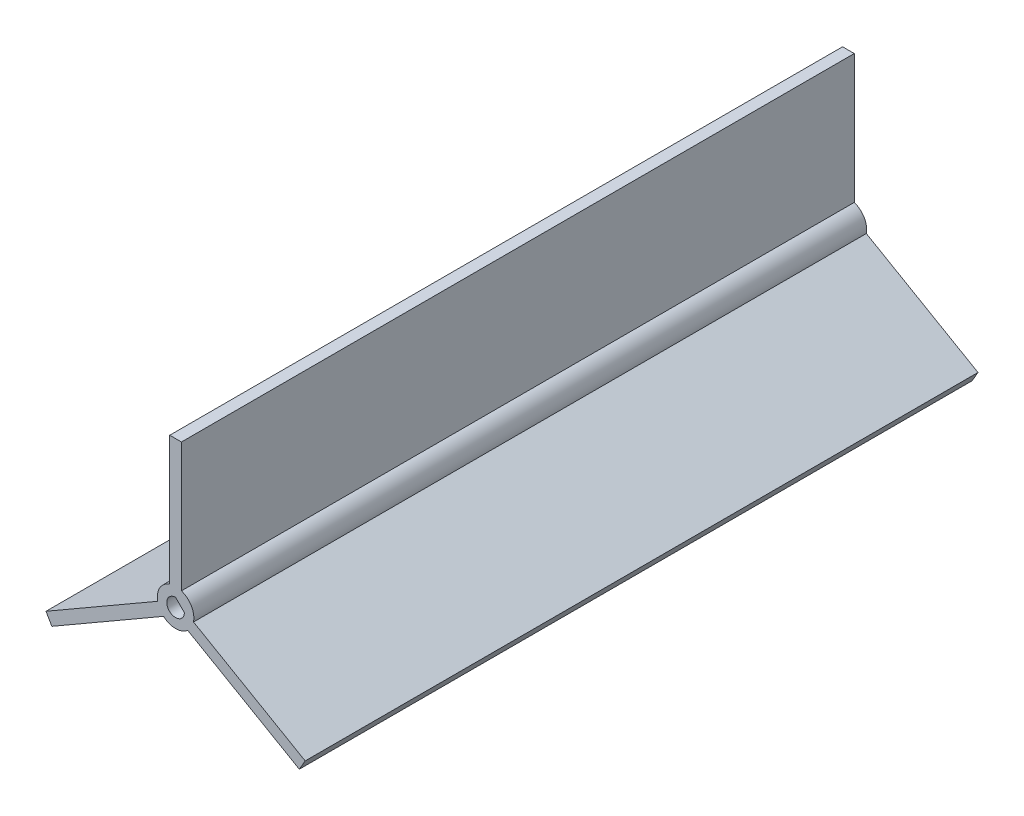
SolidWorks part; units mm, degrees
material "ABS"
ref_plane "Front Plane" through (0, 0, 0) normal (0, 0, 1) x (1, 0, 0)
ref_plane "Top Plane" through (0, 0, 0) normal (0, 1, 0) x (1, 0, 0)
ref_plane "Right Plane" through (0, 0, 0) normal (1, 0, 0) x (0, 0, -1)
sketch "Sketch1" plane through (0, 0, 0) normal (0, 0, 1) x (1, 0, 0)
  line L0 (0, 0) -> (0, 63.5)
  line L1 (0, 0) -> (54.9926, -31.75)
  line L2 (54.9926, -31.75) -> (0, 0)
  line L3 (0, 0) -> (-54.9926, -31.75)
  line L4 (2.54, 1.4665) -> (2.54, 63.5)
  line L5 (-2.54, 1.4665) -> (-56.2626, -29.5503)
  line L6 (-2.54, 1.4665) -> (-2.54, 63.5)
  line L7 (0, -2.9329) -> (-53.7226, -33.9497)
  line L8 (0, -2.9329) -> (53.7226, -33.9497)
  line L9 (2.54, 1.4665) -> (56.2626, -29.5503)
  line L10 (1.27, -2.1997) -> (-53.7226, -33.9497) construction
  line L11 (-1.27, -2.1997) -> (53.7226, -33.9497) construction
  line L12 (-1.27, 2.1997) -> (-56.2626, -29.5503) construction
  line L13 (-2.54, 0) -> (-2.54, 63.5) construction
  line L14 (1.27, 2.1997) -> (56.2626, -29.5503) construction
  line L15 (2.54, 0) -> (2.54, 63.5) construction
  line L16 (56.2626, -29.5503) -> (53.7226, -33.9497)
  line L17 (-56.2626, -29.5503) -> (-53.7226, -33.9497)
  line L18 (-2.54, 63.5) -> (2.54, 63.5)
  circle A0 centre (0, 0) radius 63.5 construction
  circle A1 centre (0, 0) radius 7.9375
  dimension "D1" = 120
  dimension "D3" = 127
  dimension "D4" = 15.875
  dimension "D2" = 120
  dimension "D5" = 2.54
  dimension "D6" = 2.54
  dimension "D7" = 2.54
  dimension "D8" = 2.54
extrude "Boss-Extrude1" add sketch "Sketch1" along normal blind 292.1 contours L6 A1 L5 | L7 A1 L8 | L9 A1 L4 | L3 A1 L7 L8 L1 | L0 A1 L6 L5 L3 | L4 A1 L0 L1 L9 | A1 L4 L18 L0 | A1 L0 L18 L6 | A1 L5 L17 L3 | A1 L3 L17 L7 | A1 L8 L16 L2 | A1 L2 L16 L9
sketch "Sketch2" plane through (0, 0, 292.1) normal (0, 0, 1) x (1, 0, 0)
  line L0 (0, 3.81) -> (3.81, 0)
  arc A0 (0, 3.81) -> (3.81, 0) centre (0, 0) ccw
  dimension "D1" = 7.62
extrude "Cut-Extrude1" cut sketch "Sketch2" against normal through all both and the other way through all
